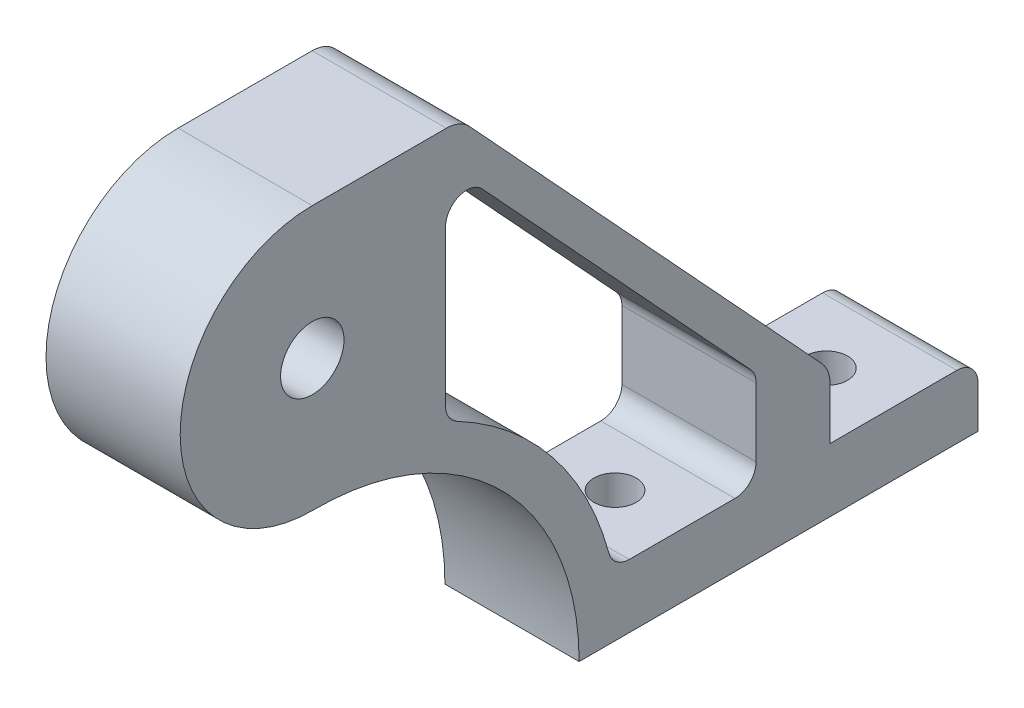
SolidWorks part; units mm, degrees
ref_plane "Front Plane" through (0, 0, 0) normal (0, 0, 1) x (1, 0, 0)
ref_plane "Top Plane" through (0, 0, 0) normal (0, 1, 0) x (1, 0, 0)
ref_plane "Right Plane" through (0, 0, 0) normal (1, 0, 0) x (0, 0, -1)
sketch "Sketch1" plane through (0, 0, 0) normal (1, 0, 0) x (0, 0, -1)
  line L0 (49.2041, 10.9568) -> (15.8909, 47.0352)
  line L3 (1, 48) -> (13.6868, 48)
  line L4 (50, 4.0009) -> (50, 8.9217)
  line L11 (50, 4.0009) -> (62, 4.0009)
  line L16 (64, 2.0009) -> (64, -1.9991)
  line L18 (26.2541, -1.9991) -> (64, -1.9991)
  line L19 (42.4694, 13.8283) -> (17.0838, 41.321)
  line L20 (13.6144, 39.9642) -> (13.6144, 25.2516)
  line L21 (43, 12.4715) -> (43, 6.0009)
  line L22 (41, 4.0009) -> (31, 4.0009)
  arc A0 (1.0847, 23.0003) -> (26.2541, -1.9991) centre (1.2541, -1.9991) cw
  arc A3 (1.0847, 23.0003) -> (1, 48) centre (1, 35.5) cw
  circle A4 centre (1, 35.5) radius 3
  arc A5 (29.0686, 5.4814) -> (14.682, 23.4822) centre (1.2541, -1.9991) ccw
  arc A6 (42.4694, 13.8283) -> (43, 12.4715) centre (41, 12.4715) cw
  arc A7 (43, 6.0009) -> (41, 4.0009) centre (41, 6.0009) cw
  arc A8 (31, 4.0009) -> (29.0686, 5.4814) centre (31, 6.0009) cw
  arc A9 (13.6144, 25.2516) -> (14.682, 23.4822) centre (15.6144, 25.2516) ccw
  arc A10 (17.0838, 41.321) -> (13.6144, 39.9642) centre (15.6144, 39.9642) ccw
  arc A11 (62, 4.0009) -> (64, 2.0009) centre (62, 2.0009) cw
  arc A12 (49.2041, 10.9568) -> (50, 8.9217) centre (47, 8.9217) cw
  arc A13 (15.8909, 47.0352) -> (13.6868, 48) centre (13.6868, 45) ccw
  point P1 (56, 4.0009)
  point P29 (64, 4.0009)
  point P30 (36, 4.0009)
  point P33 (64, 4.0009)
  point P36 (15, 48)
  dimension "D7" = 25
  dimension "D5" = 6
  dimension "D1" = 6
  dimension "D6" = 3
  dimension "D9" = 20
  dimension "D8" = 2
  dimension "D12" = 3
  dimension "D13" = 3
  dimension "D2" = 55
  dimension "D3" = 14
  dimension "D4" = 14
  dimension "D10" = 5
  dimension "D11" = 5
  dimension "D14" = 6
extrude "Boss-Extrude2" add sketch "Sketch1" along normal blind 12.7
sketch "Croquis3" plane through (0, 4.0009, 0) normal (0, 1, 0) x (1, 0, 0)
  line L0 (12.7, 62) -> (0, 62) construction
  line L2 (0, 62) -> (0, 50) construction
  circle A0 centre (6.35, 56) radius 2
  circle A1 centre (6.35, 36) radius 2
  dimension "D1" = 6
  dimension "D2" = 6.35
  dimension "D3" = 20
extrude "Cortar-Extruir2" cut sketch "Croquis3" against normal blind 25
